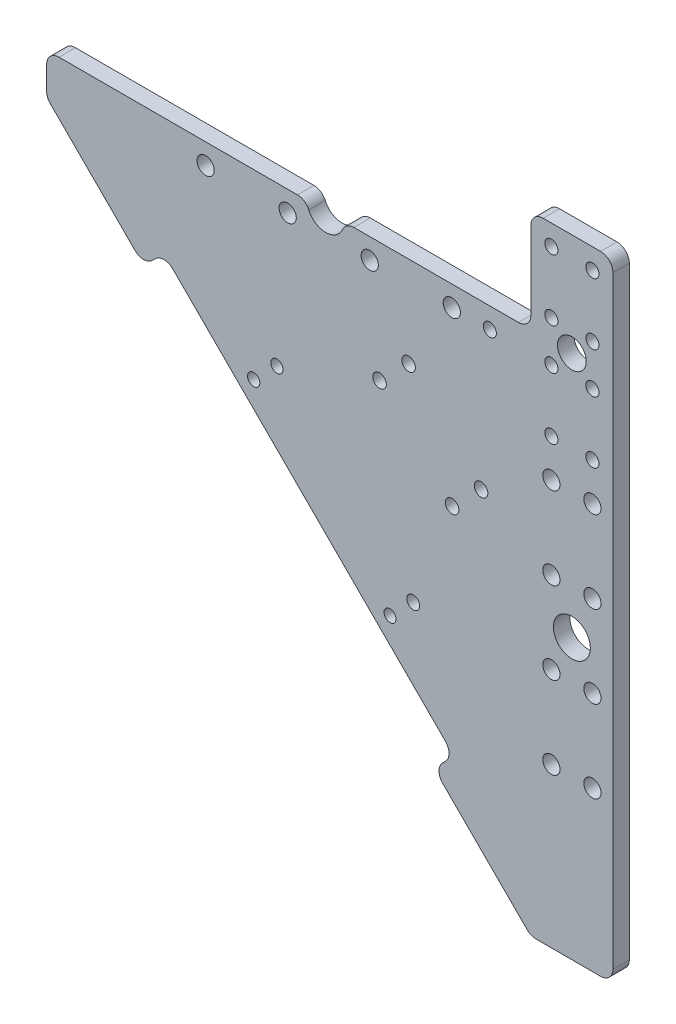
SolidWorks part; units mm, degrees
material "Thornel Mat VMA"
ref_plane "前视基准面" through (0, 0, 0) normal (0, 0, 1) x (1, 0, 0)
ref_plane "上视基准面" through (0, 0, 0) normal (0, 1, 0) x (1, 0, 0)
ref_plane "右视基准面" through (0, 0, 0) normal (1, 0, 0) x (0, 0, -1)
other "Configuration Table"
sketch "草图1" plane through (0, 0, 0) normal (0, 0, 1) x (1, 0, 0)
  line L0 (-128, -10) -> (-10, -128)
  line L5 (-10, 10) -> (10, 10)
  line L6 (-10, 10) -> (-10, -10)
  line L11 (-10, -10) -> (10, -10)
  line L12 (10, 10) -> (10, -10)
  line L13 (-10, 10) -> (10, -10) construction
  line L14 (-10, -10) -> (10, 10) construction
  line L15 (-10, -128) -> (10, -128)
  line L16 (-10, -128) -> (-10, -10)
  line L17 (-10, -10) -> (10, -10)
  line L18 (10, -128) -> (10, -10)
  line L19 (-10, -128) -> (10, -10) construction
  line L20 (-10, -10) -> (10, -128) construction
  line L21 (-128, 10) -> (-10, 10)
  line L22 (-128, 10) -> (-128, -10)
  line L23 (-128, -10) -> (-10, -10)
  line L24 (-10, 10) -> (-10, -10)
  line L25 (-128, 10) -> (-10, -10) construction
  line L26 (-128, -10) -> (-10, 10) construction
  circle A1 centre (-46.8744, -29.1967) radius 1.65 construction
  circle A2 centre (-29.1967, -46.8744) radius 1.65 construction
  circle A3 centre (-22.1256, -39.8033) radius 1.65 construction
  circle A4 centre (-39.8033, -22.1256) radius 1.65 construction
  circle A5 centre (-46.8744, -29.1967) radius 1.65
  circle A6 centre (-29.1967, -46.8744) radius 1.65
  circle A7 centre (-22.1256, -39.8033) radius 1.65
  circle A8 centre (-39.8033, -22.1256) radius 1.65
  circle A9 centre (-77.5485, -44.3145) radius 1.5 construction
  circle A10 centre (-77.5485, -44.3145) radius 1.5
  circle A11 centre (-44.3145, -77.5485) radius 1.4628 construction
  circle A12 centre (-38.6576, -71.8917) radius 1.5829 construction
  circle A13 centre (-71.8917, -38.6576) radius 1.5 construction
  circle A14 centre (-44.3145, -77.5485) radius 1.4628
  circle A15 centre (-38.6576, -71.8917) radius 1.5829
  circle A16 centre (-77.5485, -44.3145) radius 1.5
  circle A17 centre (-71.8917, -38.6576) radius 1.5
  point P0 (0, 0)
  point P6 (0, -69)
  point P7 (-69, 0)
  dimension "D1" = 20
  dimension "D2" = 20
  dimension "D3" = 118
  dimension "D4" = 118
extrude "凸台-拉伸1" add sketch "草图1" along normal blind 4 contours L22 L23 L6 L21 | L12 L5 L6 L11 | L15 L18 L11 L16 | L23 L0 L16
sketch "草图3" plane through (0, 0, 4) normal (0, 0, 1) x (1, 0, 0)
  line L1 (-5, 5) -> (5, 5) construction
  line L2 (-5, 5) -> (-5, -5) construction
  line L3 (-5, -5) -> (5, -5) construction
  line L4 (5, 5) -> (5, -5) construction
  line L5 (-5, 5) -> (5, -5) construction
  line L6 (-5, -5) -> (5, 5) construction
  circle A0 centre (0, 0) radius 3.5
  circle A1 centre (5, 5) radius 1.6
  circle A2 centre (-5, 5) radius 1.6
  circle A3 centre (-5, -5) radius 1.6
  circle A4 centre (5, -5) radius 1.6
  circle A5 centre (-20, -5) radius 1.6
  circle A6 centre (-5, -20) radius 1.6
  circle A7 centre (5, -20) radius 1.6
  circle A8 centre (5, 20) radius 1.6
  circle A9 centre (-5, 20) radius 1.6
  circle A10 centre (20, -5) radius 1.6
  circle A11 centre (20, 5) radius 1.6
  circle A12 centre (-20, 5) radius 1.6
  dimension "D1" = 10
  dimension "D5" = 3.2
  dimension "D10" = 20
  dimension "D11" = 20
  dimension "D13" = 3.2
  dimension "D15" = 3.2
  dimension "D2" = 10
  dimension "D3" = 2
  dimension "D4" = 2
  dimension "D6" = 2
  dimension "D7" = 2
  dimension "D8" = 2
  dimension "D9" = 2
extrude "切除-拉伸1" cut sketch "草图3" against normal blind 4
sketch "草图4" plane through (0, 0, 4) normal (0, 0, 1) x (1, 0, 0)
  line L1 (-128, 10) -> (10, 10) construction
  circle A0 centre (0, -60) radius 4.5
  circle A1 centre (-5, -29.2639) radius 2.1
  circle A2 centre (5, -29.2639) radius 2.1
  circle A3 centre (5, -49.2639) radius 2.1
  circle A4 centre (5, -69.2639) radius 2.1
  circle A5 centre (5, -89.2639) radius 2.1
  circle A6 centre (-5, -49.2639) radius 2.1
  circle A7 centre (-5, -69.2639) radius 2.1
  circle A8 centre (-5, -89.2639) radius 2.1
  circle A9 centre (-89.2639, -5) radius 2.1
  circle A10 centre (-69.2639, -5) radius 2.1
  circle A11 centre (-49.2639, -5) radius 2.1
  circle A12 centre (-89.2639, 5) radius 2.1
  circle A13 centre (-69.2639, 5) radius 2.1
  circle A14 centre (-49.2639, 5) radius 2.1
  circle A15 centre (-29.2639, 5) radius 2.1
  circle A16 centre (-29.2639, -5) radius 2.1
  circle A17 centre (-60, 0) radius 4.5
  dimension "D1" = 60
  dimension "D4" = 5
  dimension "D5" = 4.2
  dimension "D6" = 10
  dimension "D7" = 5
  dimension "D2" = 2
  dimension "D3" = 4
extrude "切除-拉伸2" cut sketch "草图4" against normal blind 4
sketch "草图10" plane through (0, 0, 4) normal (0, 0, 1) x (1, 0, 0)
  line L0 (10, 10) -> (-69, -69) construction
  line L1 (-128, -10) -> (-10, -128) construction
  line L2 (-45.8776, -28.1999) -> (-38.8065, -21.1289) construction
  line L3 (-45.8776, -28.1999) -> (-28.1999, -45.8776) construction
  line L4 (-38.8065, -21.1289) -> (-21.1289, -38.8065) construction
  line L5 (-28.1999, -45.8776) -> (-21.1289, -38.8065) construction
  line L6 (-45.8776, -28.1999) -> (-21.1289, -38.8065) construction
  line L7 (-38.8065, -21.1289) -> (-28.1999, -45.8776) construction
  line L8 (-72.5497, -42.4976) -> (-66.8928, -36.8408) construction
  line L9 (-72.5497, -42.4976) -> (-42.4976, -72.5497) construction
  line L10 (-66.8928, -36.8408) -> (-36.8408, -66.8928) construction
  line L11 (-42.4976, -72.5497) -> (-36.8408, -66.8928) construction
  line L12 (-72.5497, -42.4976) -> (-36.8408, -66.8928) construction
  line L13 (-66.8928, -36.8408) -> (-42.4976, -72.5497) construction
  circle A0 centre (-36.8408, -66.8928) radius 1.5
  circle A1 centre (-42.4976, -72.5497) radius 1.5
  circle A2 centre (-72.5497, -42.4976) radius 1.5
  circle A3 centre (-66.8928, -36.8408) radius 1.5
  circle A4 centre (-28.1999, -45.8776) radius 2
  circle A5 centre (-21.1289, -38.8065) radius 2
  circle A6 centre (-38.8065, -21.1289) radius 2
  circle A7 centre (-45.8776, -28.1999) radius 2
  point P6 (-33.5032, -33.5032)
  point P7 (-54.6952, -54.6952)
  dimension "D7" = 3
  dimension "D8" = 4
  dimension "D1" = 25
  dimension "D2" = 10
  dimension "D3" = 45.2
  dimension "D4" = 42.5
  dimension "D5" = 8
  dimension "D6" = 29.97
extrude "切除-拉伸6" [suppressed] cut sketch "草图10" against normal blind 4
sketch "草图11" plane through (0, 0, 4) normal (0, 0, 1) x (1, 0, 0)
  line L0 (0, 0) -> (-69, -69)
  line L1 (-128, -10) -> (-10, -128) construction
  line L2 (-99.4056, -28.6949) -> (-104.3553, -33.6447)
  line L3 (-99.4056, -28.6949) -> (-28.6949, -99.4056)
  line L4 (-104.3553, -33.6447) -> (-33.6447, -104.3553)
  line L5 (-28.6949, -99.4056) -> (-33.6447, -104.3553)
  line L6 (-99.4056, -28.6949) -> (-33.6447, -104.3553) construction
  line L7 (-104.3553, -33.6447) -> (-28.6949, -99.4056) construction
  point P5 (-65.0967, -65.0967)
  point P6 (-66.5251, -66.5251)
  line M40 (-128, -10) -> (-10, -128)
  dimension "D1" = 7
  dimension "D2" = 100
extrude "切除-拉伸7" cut sketch "草图11" against normal blind 4 contours L3 L2 L0 M40 | L5 L3 L0 M40
sketch "草图12" plane through (0, 0, 4) normal (0, 0, 1) x (1, 0, 0)
  line L0 (-128, 10) -> (-10, 10)
  line L1 (-128, 10) -> (-128, 0)
  line L2 (-10, 10) -> (-10, 0)
  line L3 (-128, 0) -> (-10, 0)
  line L4 (-128, 10) -> (10, 10) construction
  dimension "D1" = 10
  dimension "D2" = 118
extrude "切除-拉伸8" cut sketch "草图12" against normal blind 4
sketch "草图13" plane through (0, 0, 4) normal (0, 0, 1) x (1, 0, 0)
  line L1 (-10, 25) -> (10, 25)
  line L2 (-10, 25) -> (-10, 10)
  line L3 (-10, 10) -> (10, 10)
  line L4 (10, 25) -> (10, 10)
  line L5 (-10, 25) -> (10, 10) construction
  line L6 (-10, 10) -> (10, 25) construction
  circle A0 centre (-5, 20) radius 1.6
  circle A1 centre (5, 20) radius 1.6
  point P0 (0, 17.5)
  dimension "D3" = 5
  dimension "D4" = 5
  dimension "D5" = 3.2
  dimension "D1" = 15
  dimension "D2" = 10
extrude "凸台-拉伸4" add sketch "草图13" against normal blind 4
fillet "圆角4" radius 3 13 edges at (-128, -10, 2) (-104.3553, -33.6447, 2) (-99.4056, -28.6949, 2) (-28.6949, -99.4056, 2) (-33.6447, -104.3553, 2) (-10, -128, 2) (10, -128, 2) (-10, 0, 2) (-55.5, 0, 2) (-64.5, 0, 2) (-128, 0, 2) (10, 25, 2) (-10, 25, 2)
